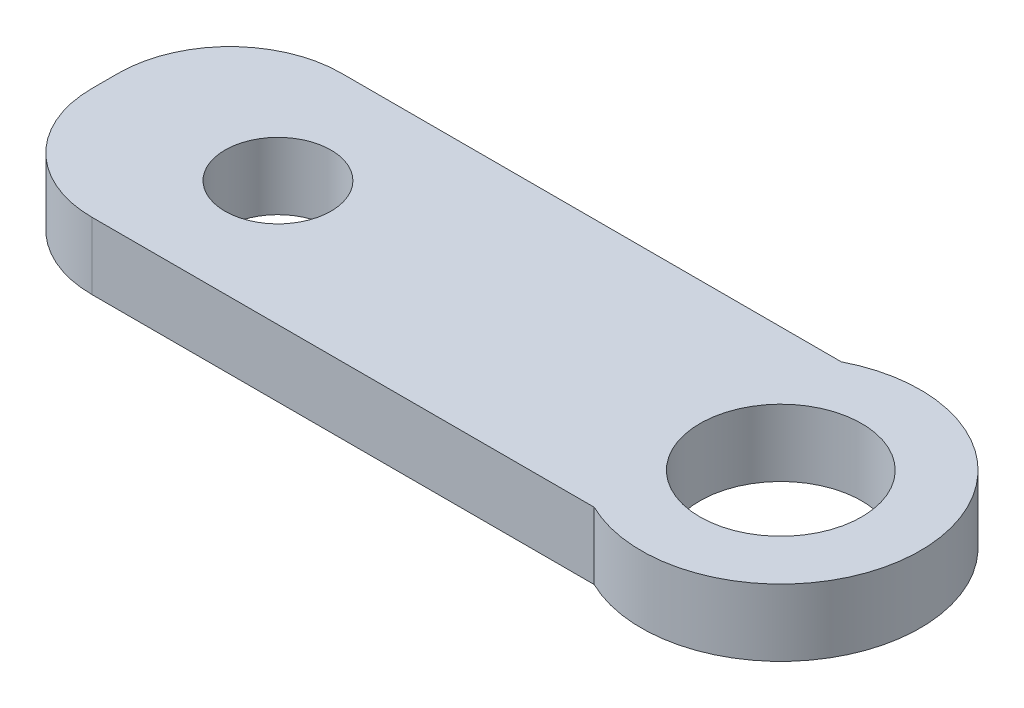
SolidWorks part; units mm, degrees
ref_plane "前视基准面" through (0, 0, 0) normal (0, 0, 1) x (1, 0, 0)
ref_plane "上视基准面" through (0, 0, 0) normal (0, 1, 0) x (1, 0, 0)
ref_plane "右视基准面" through (0, 0, 0) normal (1, 0, 0) x (0, 0, -1)
sketch "草图1" plane through (0, 0, 0) normal (0, 1, 0) x (1, 0, 0)
  line L1 (-1.097, -2.2465) -> (-12.097, -2.2465)
  line L3 (-1.1407, 2.2246) -> (-12.097, 2.2246)
  line L4 (-12.097, -2.2465) -> (-12.097, 2.2246)
  arc A0 (-1.097, -2.2465) -> (-1.1407, 2.2246) centre (0, 0) ccw
  dimension "D1" = 5
  dimension "D2" = 11
extrude "凸台-拉伸1" add sketch "草图1" along normal blind 1.2
sketch "草图2" plane through (0, 1.2, 0) normal (0, 1, 0) x (1, 0, 0)
  circle A0 centre (0, 0) radius 1.45
  dimension "D1" = 2.9
extrude "切除-拉伸1" cut sketch "草图2" against normal through all
fillet "圆角1" radius 2 2 edges at (-12.097, 0.6, -2.2246) (-12.097, 0.6, 2.2465)
sketch "草图3" plane through (0, 1.2, 0) normal (0, 1, 0) x (1, 0, 0)
  line L1 (-12.097, 0.2246) -> (-12.097, -0.2465) construction
  circle A0 centre (-9, -0.0109) radius 0.95
  circle A1 centre (0, 0) radius 1.45 construction
  point P2 (0, 0)
  point P6 (-12.097, -0.0109)
  dimension "D1" = 1.9
  dimension "D3" = 0
  dimension "D2" = 9
extrude "切除-拉伸2" cut sketch "草图3" against normal through all
